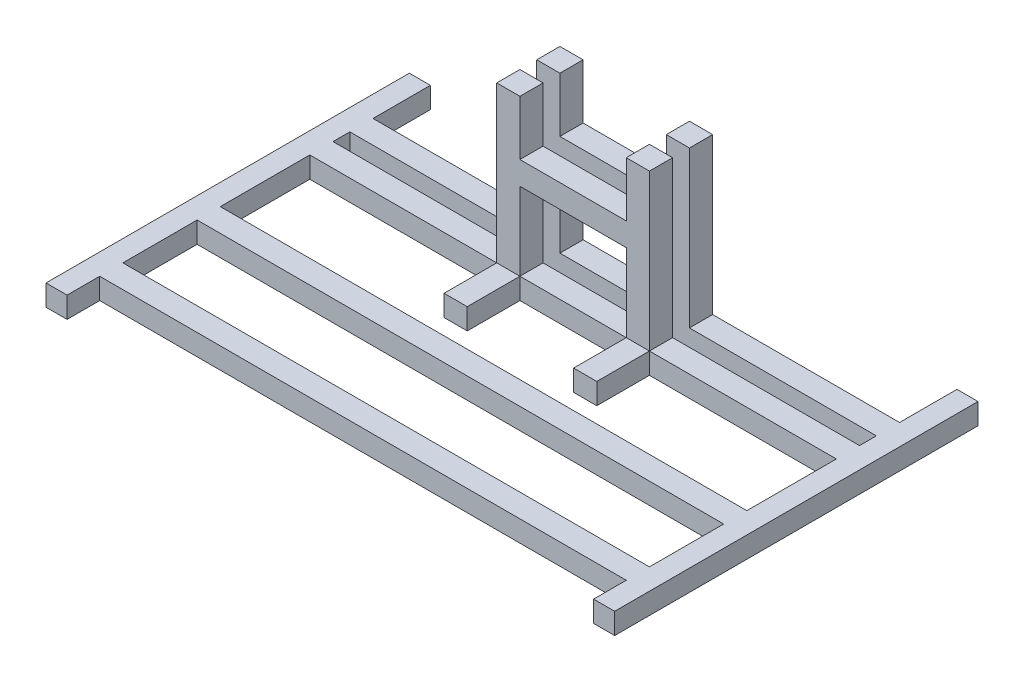
SolidWorks part; units mm, degrees
ref_plane "Front Plane" through (0, 0, 0) normal (0, 0, 1) x (1, 0, 0)
ref_plane "Top Plane" through (0, 0, 0) normal (0, 1, 0) x (1, 0, 0)
ref_plane "Right Plane" through (0, 0, 0) normal (1, 0, 0) x (0, 0, -1)
sketch "Sketch1" plane through (0, 0, 0) normal (0, 1, 0) x (1, 0, 0)
  line L0 (-500, 345) -> (-500, -345)
  line L1 (-540, 345) -> (-500, 345)
  line L2 (-540, 345) -> (-540, -345)
  line L3 (-540, -345) -> (-500, -345)
  line L4 (540, 345) -> (540, -345)
  line L5 (-540, 345) -> (540, -345) construction
  line L6 (-540, -345) -> (540, 345) construction
  line L7 (500, 345) -> (500, -345)
  line L8 (500, 345) -> (540, 345)
  line L9 (500, -345) -> (540, -345)
  line L10 (-500, 236) -> (500, 236)
  line L11 (-500, 192) -> (500, 192)
  line L12 (-500, 160) -> (500, 160)
  line L13 (-500, 116) -> (500, 116)
  line L14 (-500, -54) -> (500, -54)
  line L15 (-500, -98) -> (500, -98)
  line L16 (-500, -239) -> (500, -239)
  line L17 (-500, -283) -> (500, -283)
  line L18 (-500, -239) -> (-500, -283)
  line L19 (500, -239) -> (500, -283)
  line L20 (500, -54) -> (500, -98)
  line L21 (-500, -54) -> (-500, -98)
  line L22 (-500, 160) -> (-500, 116)
  line L23 (500, 160) -> (500, 116)
  line L24 (500, 236) -> (500, 192)
  line L25 (-500, 236) -> (-500, 192)
  point P0 (0, 0)
  dimension "D1" = 690
  dimension "D2" = 1080
  dimension "D3" = 40
  dimension "D4" = 40
  dimension "D5" = 44
  dimension "D6" = 44
  dimension "D7" = 44
  dimension "D8" = 44
  dimension "D9" = 106
  dimension "D10" = 229
  dimension "D11" = 258
  dimension "D12" = 120
extrude "Boss-Extrude1" add sketch "Sketch1" along normal blind 40 contours L0 L15 L7 L14 | L0 L11 L7 L10 | L16 L19 L17 L18 | L12 L23 L13 L22
sketch "Sketch2" plane through (0, 40, 0) normal (0, 1, 0) x (1, 0, 0)
  line L0 (-500, 236) -> (500, 236) construction
  line L1 (-145, 236) -> (-101, 236)
  line L2 (-145, 236) -> (-145, 192)
  line L3 (-145, 192) -> (-101, 192)
  line L4 (-101, 236) -> (-101, 192)
  line L5 (-500, 192) -> (500, 192) construction
  line L6 (-500, 160) -> (500, 160) construction
  line L7 (101, 236) -> (145, 236)
  line L8 (101, 236) -> (101, 192)
  line L9 (101, 192) -> (145, 192)
  line L10 (145, 236) -> (145, 192)
  line L11 (-145, 160) -> (-101, 160)
  line L12 (-145, 160) -> (-145, 116)
  line L13 (-145, 116) -> (-101, 116)
  line L14 (-101, 160) -> (-101, 116)
  line L15 (-500, 116) -> (500, 116) construction
  line L16 (-540, 345) -> (-540, -345) construction
  line L17 (101, 160) -> (145, 160)
  line L18 (101, 160) -> (101, 116)
  line L19 (101, 116) -> (145, 116)
  line L20 (145, 160) -> (145, 116)
  line L21 (540, 345) -> (540, -345) construction
  dimension "D1" = 44
  dimension "D2" = 44
  dimension "D3" = 44
  dimension "D4" = 44
  dimension "D5" = 395
  dimension "D6" = 395
  dimension "D7" = 395
  dimension "D8" = 395
extrude "Boss-Extrude2" add sketch "Sketch2" along normal blind 296
sketch "Sketch3" plane through (0, 0, -116) normal (0, 0, 1) x (1, 0, 0)
  line L0 (-500, 0) -> (500, 0) construction
  line L1 (-145, 40) -> (-101, 40)
  line L2 (-145, 40) -> (-145, 0)
  line L3 (-145, 0) -> (-101, 0)
  line L4 (-101, 40) -> (-101, 0)
  line L6 (101, 40) -> (145, 40)
  line L7 (101, 40) -> (101, 0)
  line L8 (101, 0) -> (145, 0)
  line L9 (145, 40) -> (145, 0)
extrude "Boss-Extrude3" add sketch "Sketch3" along normal blind 100
sketch "Sketch4" plane through (-101, 0, 0) normal (1, 0, 0) x (0, 0, -1)
  line L0 (116, 336) -> (116, 40) construction
  line L1 (116, 232) -> (160, 232)
  line L2 (116, 232) -> (116, 188)
  line L3 (116, 188) -> (160, 188)
  line L4 (160, 232) -> (160, 188)
  line L5 (160, 336) -> (160, 40) construction
  line L6 (192, 336) -> (192, 40) construction
  line L7 (192, 232) -> (236, 232)
  line L8 (192, 232) -> (192, 188)
  line L9 (192, 188) -> (236, 188)
  line L10 (236, 232) -> (236, 188)
  line L11 (236, 336) -> (236, 40) construction
  dimension "D1" = 44
  dimension "D2" = 44
  dimension "D3" = 0
extrude "Boss-Extrude4" add sketch "Sketch4" along normal blind 209
